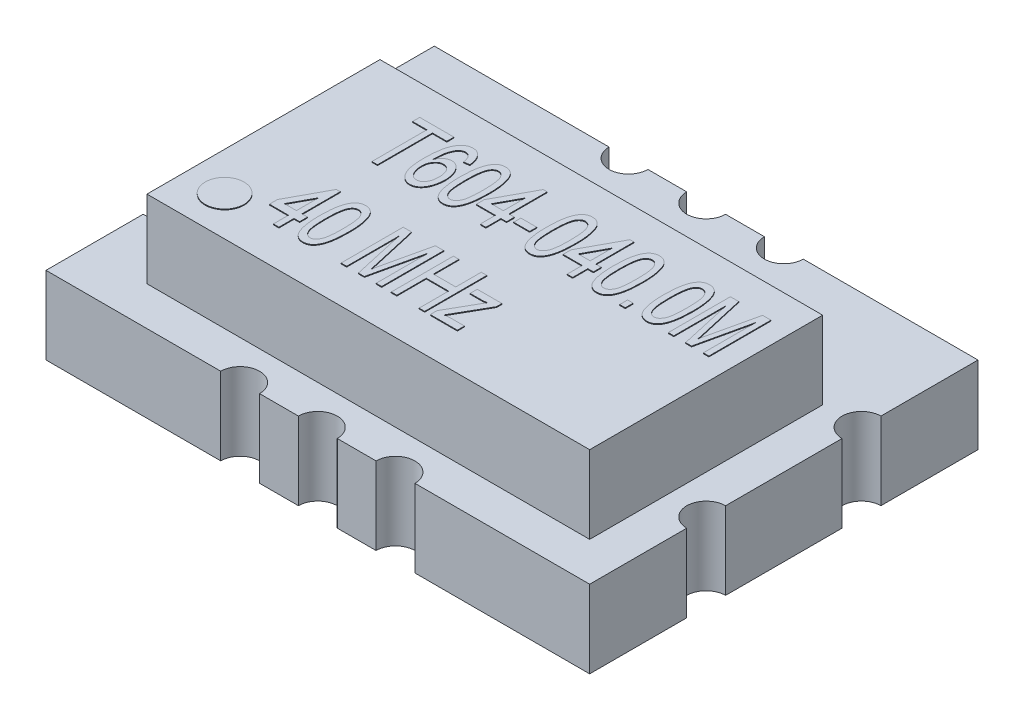
SolidWorks part; units mm, degrees
ref_plane "Z" through (0, 0, 0) normal (0, 0, 1) x (1, 0, 0)
ref_plane "Y" through (0, 0, 0) normal (0, 1, 0) x (1, 0, 0)
ref_plane "X" through (0, 0, 0) normal (1, 0, 0) x (0, 0, -1)
sketch "Эскиз - Плата основа" plane through (0, 0, 0) normal (0, 1, 0) x (1, 0, 0)
  line L0 (0, 2.5) -> (0, -2.5) construction
  line L1 (-3.5, 2.5) -> (3.5, 2.5)
  line L2 (-3.5, 2.5) -> (-3.5, -2.5)
  line L3 (-3.5, -2.5) -> (3.5, -2.5)
  line L4 (3.5, 2.5) -> (3.5, -2.5)
  line L5 (-3.5, 2.5) -> (3.5, -2.5) construction
  line L6 (-3.5, -2.5) -> (3.5, 2.5) construction
  line L7 (3.5, 0) -> (-3.5, 0) construction
  point P0 (0, 0)
  dimension "D1" = 5
  dimension "D2" = 7
extrude "Бобышка - Плата основка" add sketch "Эскиз - Плата основа" along normal blind 1
sketch "Эскиз2" plane through (0, 1, 0) normal (0, 1, 0) x (1, 0, 0)
  line L0 (3.5, 2.5) -> (-3.5, 2.5) construction
  line L1 (3.5, -2.5) -> (3.5, 2.5) construction
  line L2 (-3.5, -2.5) -> (3.5, -2.5) construction
  line L3 (-3.5, 2.5) -> (-3.5, -2.5) construction
  line L4 (0, 2.5) -> (0, -2.5) construction
  line L5 (3.5, 0) -> (-3.5, 0) construction
  circle A0 centre (0, 2.5) radius 0.25
  circle A1 centre (-1, 2.5) radius 0.25
  circle A2 centre (1, 2.5) radius 0.25
  circle A3 centre (1, -2.5) radius 0.25
  circle A4 centre (0, -2.5) radius 0.25
  circle A5 centre (-1, -2.5) radius 0.25
  circle A6 centre (-3.5, 1) radius 0.25
  circle A7 centre (-3.5, -1) radius 0.25
  circle A8 centre (3.5, -1) radius 0.25
  circle A9 centre (3.5, 1) radius 0.25
  point P0 (0, 2.5)
  point P1 (3.5, 0)
  point P4 (0, -2.5)
  point P7 (-3.5, 0)
  point P17 (1, 2.5)
  point P18 (-1, 2.5)
  point P28 (-3.5, 1)
  point P29 (-3.5, -1)
  dimension "D1" = 1
  dimension "D3" = 1
  dimension "D2" = 1
  dimension "D4" = 1
extrude "Вырез-Вытянуть1" cut sketch "Эскиз2" against normal blind 1
sketch "Эскиз3" plane through (0, 1, 0) normal (0, 1, 0) x (1, 0, 0)
  line L1 (3, 1) -> (-2.7, 1)
  line L2 (3, 1) -> (3, -2)
  line L3 (3, -2) -> (-2.7, -2)
  line L4 (-2.7, 1) -> (-2.7, -2)
  dimension "D1" = 5.7
  dimension "D2" = 3
  dimension "D3" = 0.5
  dimension "D4" = 0.5
extrude "Бобышка-Метал корпус микросхемы" add sketch "Эскиз3" along normal blind 1
sketch "Эскиз4" plane through (0, 2, 0) normal (0, 1, 0) x (1, 0, 0)
  line L0 (-2.7, -2) -> (3, -2) construction
  line L1 (-2.7, 1) -> (-2.7, -2) construction
  circle A0 centre (-2.2, -1.5) radius 0.25
  point P6 (-2.5662, -1.3504)
  dimension "D1" = 0.5
  dimension "D2" = 0.5
extrude "Бобышка-Маркер первой ножки" add sketch "Эскиз4" along normal blind 0.01
sketch "Эскиз5" plane through (0, 2, 0) normal (0, 1, 0) x (1, 0, 0)
  line L0 (-1.8, -0.1984) -> (3.2, -0.1984) construction
  line L1 (-2.7, 1) -> (-2.7, -2) construction
  text T0 "T604-040.0M \r\n40 MHz" font "Arial" height 0.8
  dimension "D1" = 0.9
extrude "Бобышка-Надпись" add sketch "Эскиз5" along normal blind 0.01
